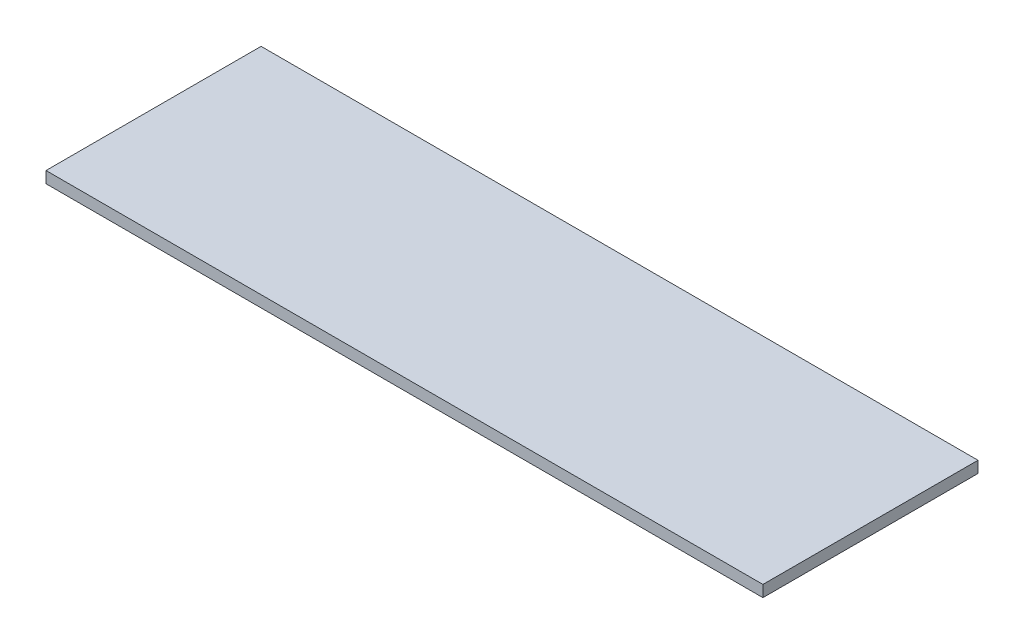
SolidWorks part; units mm, degrees
material "A-Glass Fiber"
ref_plane "Front Plane" through (0, 0, 0) normal (0, 0, 1) x (1, 0, 0)
ref_plane "Top Plane" through (0, 0, 0) normal (0, 1, 0) x (1, 0, 0)
ref_plane "Right Plane" through (0, 0, 0) normal (1, 0, 0) x (0, 0, -1)
sketch "Sketch1" plane through (0, 0, 0) normal (0, 1, 0) x (1, 0, 0)
  line L1 (-50, 15) -> (50, 15)
  line L2 (-50, 15) -> (-50, -15)
  line L3 (-50, -15) -> (50, -15)
  line L4 (50, 15) -> (50, -15)
  line L5 (-50, 15) -> (50, -15) construction
  line L6 (-50, -15) -> (50, 15) construction
  point P0 (0, 0)
  dimension "D1" = 100
  dimension "D2" = 30
extrude "Boss-Extrude1" add sketch "Sketch1" against normal blind 1.6
